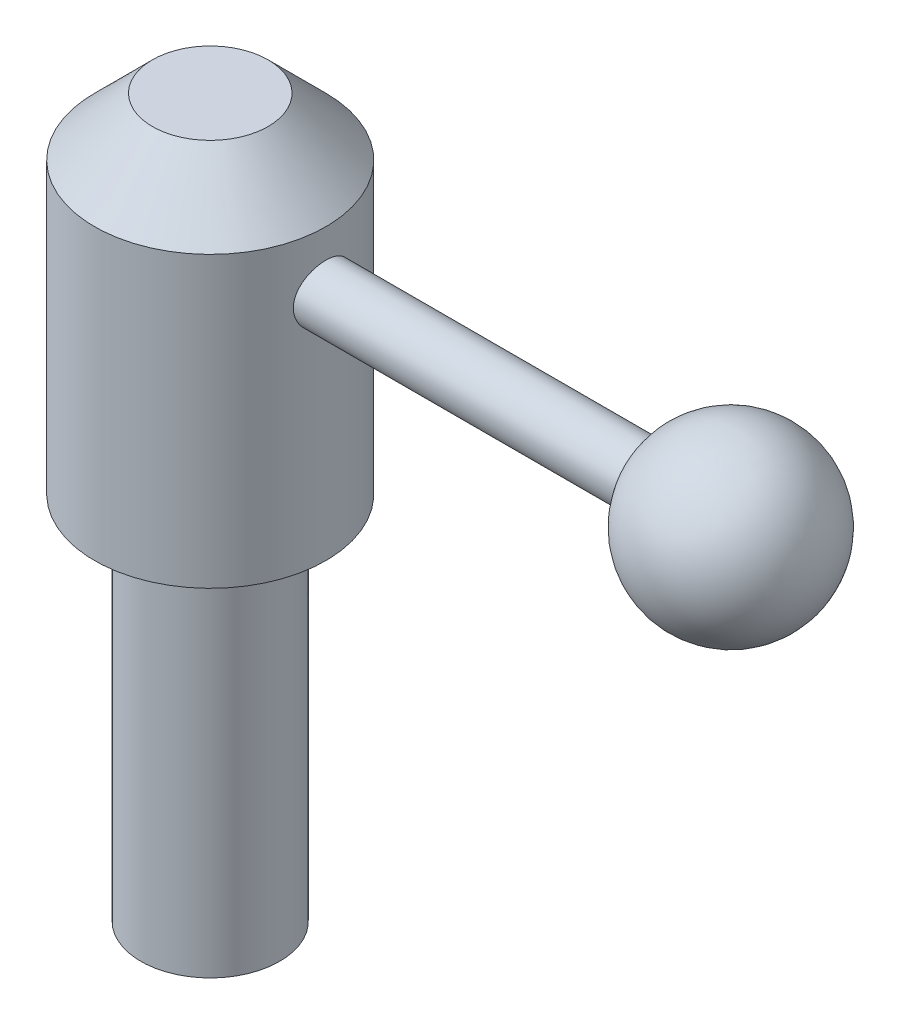
SolidWorks part; units mm, degrees
ref_plane "Front Plane" through (0, 0, 0) normal (0, 0, 1) x (1, 0, 0)
ref_plane "Top Plane" through (0, 0, 0) normal (0, 1, 0) x (1, 0, 0)
ref_plane "Right Plane" through (0, 0, 0) normal (1, 0, 0) x (0, 0, -1)
sketch "Sketch1" plane through (0, 0, 0) normal (0, 0, 1) x (1, 0, 0)
  line L0 (0, 0) -> (0, 36.9186) construction
  line L1 (0, 0) -> (-6, 0)
  line L2 (-6, 0) -> (-6, 32)
  line L3 (-6, 32) -> (-10, 32)
  line L4 (-10, 32) -> (-10, 62)
  line L5 (-10, 62) -> (0, 62)
  line L6 (0, 62) -> (0, 0)
  dimension "D1" = 30
  dimension "D2" = 32
  dimension "D3" = 6
  dimension "D4" = 10
revolve "Revolve1" add sketch "Sketch1" angle 360 about L0
chamfer "Chamfer1" distance 5 angle 45 1 edges at (0, 62, -10)
sketch "Sketch2" plane through (0, 0, 0) normal (0, 0, 1) x (1, 0, 0)
  line L0 (0, 52) -> (25.6039, 52) construction
  line L1 (-10, 32) -> (10, 32) construction
  line L2 (0, 52) -> (0, 54.5)
  line L3 (0, 54.5) -> (37.9289, 54.5)
  line L4 (0, 52) -> (52.5, 52)
  arc A0 (52.5, 52) -> (37.9289, 54.5) centre (45, 52) ccw
  point P8 (31.1558, 54.5467)
  dimension "D2" = 7.5
  dimension "D1" = 20
  dimension "D3" = 45
  dimension "D4" = 2.5
revolve "Revolve2" add sketch "Sketch2" angle 360 about L0
